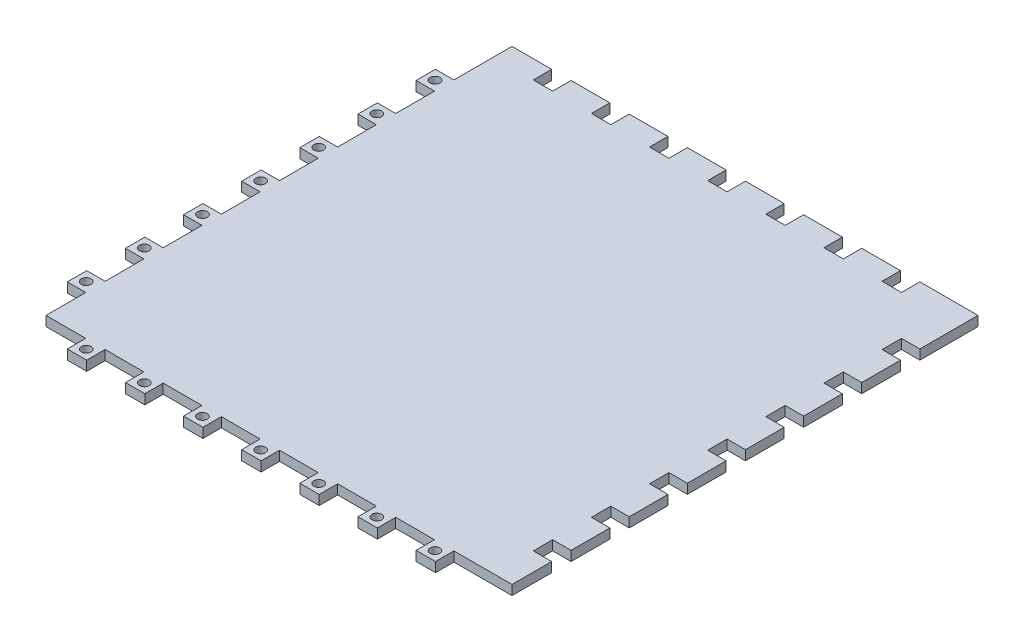
SolidWorks part; units mm, degrees
ref_plane "Спереди" through (0, 0, 0) normal (0, 0, 1) x (1, 0, 0)
ref_plane "Сверху" through (0, 0, 0) normal (0, 1, 0) x (1, 0, 0)
ref_plane "Справа" through (0, 0, 0) normal (1, 0, 0) x (0, 0, -1)
sketch "Эскиз1" plane through (0, 0, 0) normal (0, 1, 0) x (1, 0, 0)
  line L0 (25, -23.1) -> (25, -19)
  line L1 (19, -25) -> (17, -25)
  line L2 (25, -23.1) -> (25, -19)
  line L3 (25, 25) -> (19, 25)
  line L4 (-25, -19) -> (-25, -17)
  line L5 (25, 25) -> (19, 25)
  line L6 (19, 25) -> (19, 23.1)
  line L7 (25, -19) -> (23.1, -19)
  line L8 (23.1, -19) -> (23.1, -17)
  line L9 (23.1, -17) -> (25, -17)
  line L10 (25, -13) -> (23.1, -13)
  line L11 (23.1, -13) -> (23.1, -11)
  line L12 (23.1, -11) -> (25, -11)
  line L13 (25, -7) -> (23.1, -7)
  line L14 (23.1, -7) -> (23.1, -5)
  line L15 (23.1, -5) -> (25, -5)
  line L16 (25, -1) -> (23.1, -1)
  line L17 (23.1, -1) -> (23.1, 1)
  line L18 (23.1, 1) -> (25, 1)
  line L19 (25, 5) -> (23.1, 5)
  line L20 (23.1, 5) -> (23.1, 7)
  line L21 (23.1, 7) -> (25, 7)
  line L22 (25, 11) -> (23.1, 11)
  line L23 (23.1, 11) -> (23.1, 13)
  line L24 (23.1, 13) -> (25, 13)
  line L25 (25, 17) -> (23.1, 17)
  line L26 (23.1, 17) -> (23.1, 19)
  line L27 (23.1, 19) -> (25, 19)
  line L28 (19, 23.1) -> (17, 23.1)
  line L29 (17, 23.1) -> (17, 25)
  line L30 (13, 25) -> (13, 23.1)
  line L31 (13, 23.1) -> (11, 23.1)
  line L32 (11, 23.1) -> (11, 25)
  line L33 (7, 25) -> (7, 23.1)
  line L34 (7, 23.1) -> (5, 23.1)
  line L35 (5, 23.1) -> (5, 25)
  line L36 (1, 25) -> (1, 23.1)
  line L37 (1, 23.1) -> (-1, 23.1)
  line L38 (-1, 23.1) -> (-1, 25)
  line L39 (-5, 25) -> (-5, 23.1)
  line L40 (-5, 23.1) -> (-7, 23.1)
  line L41 (-7, 23.1) -> (-7, 25)
  line L42 (-11, 25) -> (-11, 23.1)
  line L43 (-11, 23.1) -> (-13, 23.1)
  line L44 (-13, 23.1) -> (-13, 25)
  line L45 (-17, 25) -> (-17, 23.1)
  line L46 (-17, 23.1) -> (-19, 23.1)
  line L47 (-19, 23.1) -> (-19, 25)
  line L48 (-19, 25) -> (-23.1, 25)
  line L49 (-23.1, 25) -> (-23.1, 19)
  line L50 (-23.1, 19) -> (-25, 19)
  line L51 (-25, 19) -> (-25, 17)
  line L52 (-25, 17) -> (-23.1, 17)
  line L53 (-23.1, 13) -> (-25, 13)
  line L54 (-25, 13) -> (-25, 11)
  line L55 (-25, 11) -> (-23.1, 11)
  line L56 (-23.1, 7) -> (-25, 7)
  line L57 (-25, 7) -> (-25, 5)
  line L58 (-25, 5) -> (-23.1, 5)
  line L59 (-23.1, 1) -> (-25, 1)
  line L60 (-25, 1) -> (-25, -1)
  line L61 (-25, -1) -> (-23.1, -1)
  line L62 (-23.1, -5) -> (-25, -5)
  line L63 (-25, -5) -> (-25, -7)
  line L64 (-25, -7) -> (-23.1, -7)
  line L65 (-23.1, -11) -> (-25, -11)
  line L66 (-25, -11) -> (-25, -13)
  line L67 (-25, -13) -> (-23.1, -13)
  line L68 (-23.1, -17) -> (-25, -17)
  line L69 (-25, -17) -> (-25, -19)
  line L70 (-25, -19) -> (-23.1, -19)
  line L71 (-23.1, -19) -> (-23.1, -23.1)
  line L72 (-23.1, 17) -> (-23.1, 13)
  line L73 (-23.1, 11) -> (-23.1, 7)
  line L74 (-23.1, 5) -> (-23.1, 1)
  line L75 (-23.1, -1) -> (-23.1, -5)
  line L76 (-23.1, -7) -> (-23.1, -11)
  line L77 (-23.1, -13) -> (-23.1, -17)
  line L78 (-17, -25) -> (-19, -25)
  line L79 (-19, -25) -> (-19, -23.1)
  line L80 (-19, -23.1) -> (-23.1, -23.1)
  line L81 (-17, -23.1) -> (-17, -25)
  line L82 (-13, -25) -> (-13, -23.1)
  line L83 (-17, -23.1) -> (-13, -23.1)
  line L84 (-11, -23.1) -> (-11, -25)
  line L85 (-7, -25) -> (-7, -23.1)
  line L86 (-11, -23.1) -> (-7, -23.1)
  line L87 (-5, -23.1) -> (-5, -25)
  line L88 (-1, -25) -> (-1, -23.1)
  line L89 (-5, -23.1) -> (-1, -23.1)
  line L90 (1, -23.1) -> (1, -25)
  line L91 (5, -25) -> (5, -23.1)
  line L92 (1, -23.1) -> (5, -23.1)
  line L93 (7, -23.1) -> (7, -25)
  line L94 (11, -25) -> (11, -23.1)
  line L95 (7, -23.1) -> (11, -23.1)
  line L96 (13, -23.1) -> (13, -25)
  line L97 (17, -25) -> (17, -23.1)
  line L98 (13, -23.1) -> (17, -23.1)
  line L99 (19, -23.1) -> (19, -25)
  line L100 (19, -23.1) -> (25, -23.1)
  line L101 (-11, -25) -> (-13, -25)
  line L102 (-5, -25) -> (-7, -25)
  line L103 (1, -25) -> (-1, -25)
  line L104 (7, -25) -> (5, -25)
  line L105 (13, -25) -> (11, -25)
  line L106 (-25, -13) -> (-25, -11)
  line L107 (-25, -7) -> (-25, -5)
  line L108 (-25, -1) -> (-25, 1)
  line L109 (-25, 5) -> (-25, 7)
  line L110 (-25, 11) -> (-25, 13)
  line L111 (-25, 17) -> (-25, 19)
  line L112 (-13, 25) -> (-17, 25)
  line L113 (-7, 25) -> (-11, 25)
  line L114 (-1, 25) -> (-5, 25)
  line L115 (5, 25) -> (1, 25)
  line L116 (11, 25) -> (7, 25)
  line L117 (17, 25) -> (13, 25)
  line L118 (25, 19) -> (25, 25)
  line L119 (25, 13) -> (25, 17)
  line L120 (25, 7) -> (25, 11)
  line L121 (25, 1) -> (25, 5)
  line L122 (25, -5) -> (25, -1)
  line L123 (25, -11) -> (25, -7)
  line L124 (25, -17) -> (25, -13)
  circle A0 centre (18, -24.05) radius 0.5
  circle A1 centre (12, -24.05) radius 0.5
  circle A2 centre (6, -24.05) radius 0.5
  circle A3 centre (0, -24.05) radius 0.5
  circle A4 centre (-6, -24.05) radius 0.5
  circle A5 centre (-12, -24.05) radius 0.5
  circle A6 centre (-18, -24.05) radius 0.5
  circle A7 centre (-24.05, -18) radius 0.5
  circle A8 centre (-24.05, -12) radius 0.5
  circle A9 centre (-24.05, -6) radius 0.5
  circle A10 centre (-24.05, 0) radius 0.5
  circle A11 centre (-24.05, 6) radius 0.5
  circle A12 centre (-24.05, 12) radius 0.5
  circle A13 centre (-24.05, 18) radius 0.5
  point P0 (0, 0)
  dimension "D1" = 7
  dimension "D3" = 7
  dimension "D2" = 7
extrude "Бобышка-Вытянуть2" add sketch "Эскиз1" along normal blind 1
